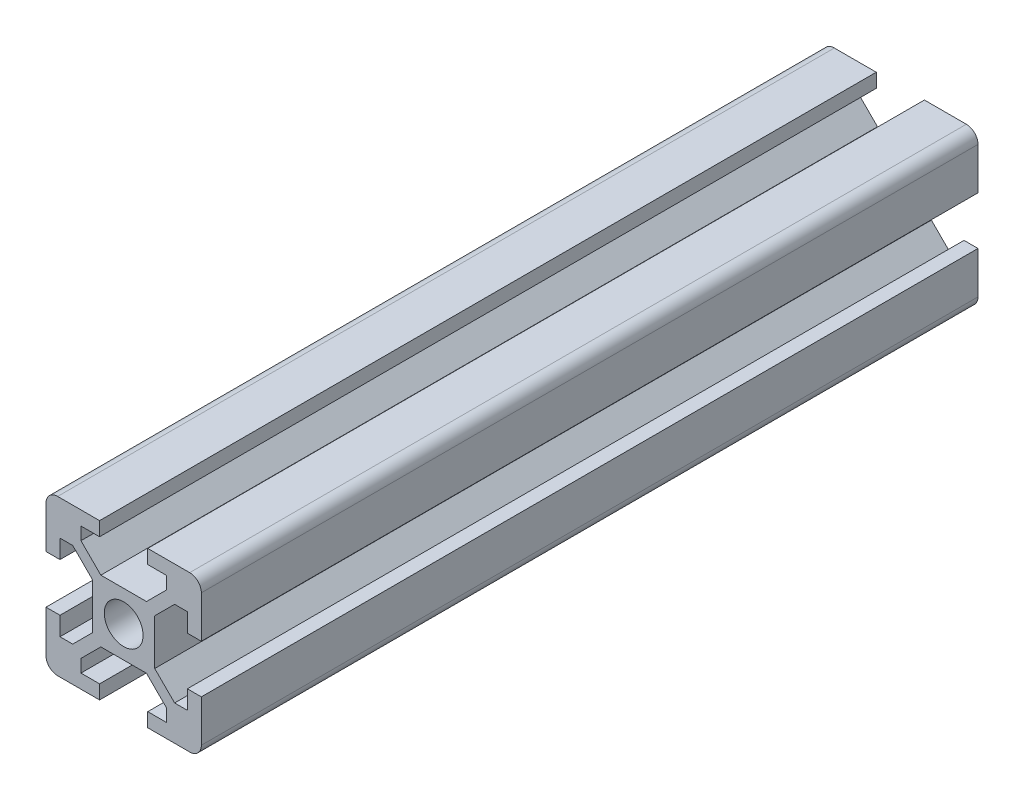
SolidWorks part; units mm, degrees
ref_plane "前视基准面" through (0, 0, 0) normal (0, 0, 1) x (1, 0, 0)
ref_plane "上视基准面" through (0, 0, 0) normal (0, 1, 0) x (1, 0, 0)
ref_plane "右视基准面" through (0, 0, 0) normal (1, 0, 0) x (0, 0, -1)
sketch "草图1" plane through (0, 0, 0) normal (0, 0, 1) x (1, 0, 0)
  line L0 (5.5, -8.2) -> (5.5, -6.5607)
  line L1 (-8.5, -10) -> (-3.1, -10)
  line L2 (-10, -8.5) -> (-10, -3.1)
  line L3 (-8.5, 10) -> (-3.1, 10)
  line L4 (10, -8.5) -> (10, -3.1)
  line L5 (-10, -10) -> (10, 10) construction
  line L6 (-10, 10) -> (10, -10) construction
  line L7 (8.2, 5.5) -> (6.5607, 5.5)
  line L8 (-2.9393, 4) -> (2.9393, 4)
  line L9 (4, 2.9393) -> (4, -2.9393)
  line L10 (2.9393, -4) -> (-2.9393, -4)
  line L11 (-4, -2.9393) -> (-4, 2.9393)
  line L12 (5.5, 6.5607) -> (5.5, 8.2)
  line L13 (6.5607, -5.5) -> (8.2, -5.5)
  line L14 (-8.2, -5.5) -> (-6.5607, -5.5)
  line L15 (-5.5, -6.5607) -> (-5.5, -8.2)
  line L16 (-5.5, 8.2) -> (-5.5, 6.5607)
  line L17 (-6.5607, 5.5) -> (-8.2, 5.5)
  line L18 (4, 2.9393) -> (6.5607, 5.5)
  line L19 (2.9393, 4) -> (5.5, 6.5607)
  line L20 (2.9393, -4) -> (5.5, -6.5607)
  line L21 (-4, 2.9393) -> (-6.5607, 5.5)
  line L22 (4, -2.9393) -> (6.5607, -5.5)
  line L23 (-2.9393, 4) -> (-5.5, 6.5607)
  line L24 (-4, -2.9393) -> (-6.5607, -5.5)
  line L25 (-2.9393, -4) -> (-5.5, -6.5607)
  line L26 (8.2, 3.1) -> (8.2, 5.5)
  line L27 (8.2, 3.1) -> (10, 3.1)
  line L28 (3.1, -8.2) -> (5.5, -8.2)
  line L29 (3.1, -8.2) -> (3.1, -10)
  line L30 (8.2, -3.1) -> (10, -3.1)
  line L31 (8.2, -3.1) -> (8.2, -5.5)
  line L32 (-3.1, -8.2) -> (-3.1, -10)
  line L33 (-3.1, -8.2) -> (-5.5, -8.2)
  line L34 (-8.2, -3.1) -> (-8.2, -5.5)
  line L35 (-8.2, -3.1) -> (-10, -3.1)
  line L36 (-8.2, 3.1) -> (-10, 3.1)
  line L37 (-8.2, 3.1) -> (-8.2, 5.5)
  line L38 (-3.1, 8.2) -> (-5.5, 8.2)
  line L39 (-3.1, 8.2) -> (-3.1, 10)
  line L40 (3.1, 8.2) -> (3.1, 10)
  line L41 (3.1, 8.2) -> (5.5, 8.2)
  line L42 (10, 3.1) -> (10, 8.5)
  line L43 (3.1, 10) -> (8.5, 10)
  line L44 (-10, 3.1) -> (-10, 8.5)
  line L45 (3.1, -10) -> (8.5, -10)
  arc A0 (8.5, -10) -> (10, -8.5) centre (8.5, -8.5) ccw
  arc A1 (-10, 8.5) -> (-8.5, 10) centre (-8.5, 8.5) cw
  arc A2 (-8.5, -10) -> (-10, -8.5) centre (-8.5, -8.5) cw
  arc A3 (8.5, 10) -> (10, 8.5) centre (8.5, 8.5) cw
  circle A4 centre (0, 0) radius 2.5
  point P0 (0, 0)
  point P39 (0, 0)
  point P56 (0, 0)
  point P73 (0, 0)
  dimension "D3" = 1.5
  dimension "D4" = 4
  dimension "D1" = 20
  dimension "D2" = 20
  dimension "D5" = 4
  dimension "D6" = 4
extrude "凸台-拉伸2" add sketch "草图1" against normal blind 100
